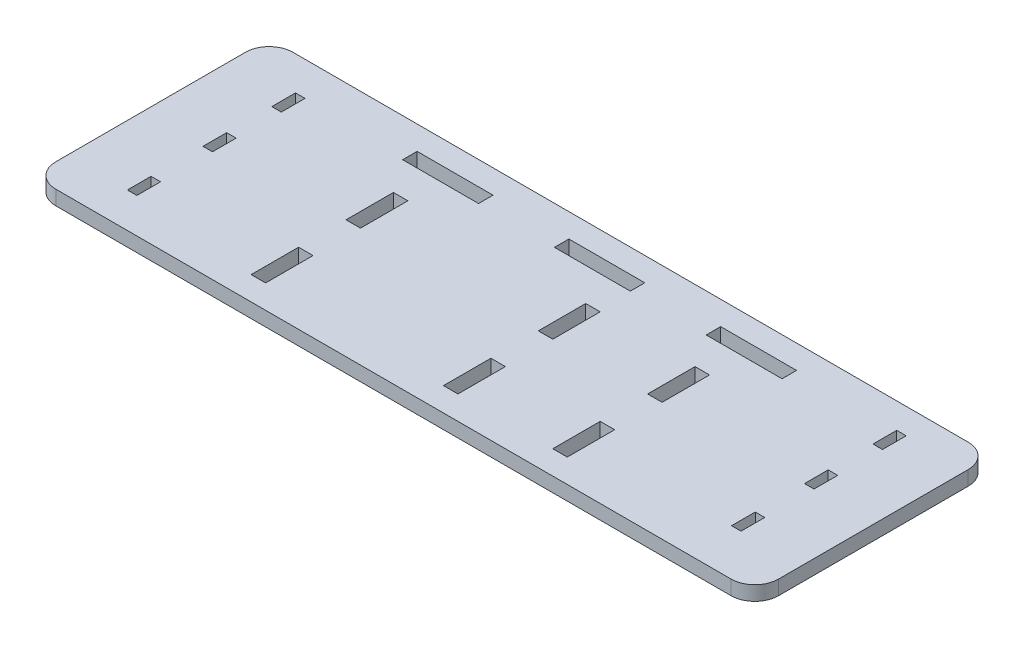
SolidWorks part; units mm, degrees
ref_plane "Front Plane" through (0, 0, 0) normal (0, 0, 1) x (1, 0, 0)
ref_plane "Top Plane" through (0, 0, 0) normal (0, 1, 0) x (1, 0, 0)
ref_plane "Right Plane" through (0, 0, 0) normal (1, 0, 0) x (0, 0, -1)
sketch "Sketch1" plane through (0, 0, 0) normal (0, 1, 0) x (1, 0, 0)
  line L0 (-232.4, 90) -> (-232.4, 83.9)
  line L1 (-294.8, 100) -> (-10, 100)
  line L2 (-304.8, 90) -> (-304.8, 10)
  line L3 (-294.8, 0) -> (-10, 0)
  line L4 (0, 90) -> (0, 10)
  line L5 (-232.4, 83.9) -> (-200.4, 83.9)
  line L6 (-200.4, 83.9) -> (-200.4, 90)
  line L7 (-200.4, 90) -> (-232.4, 90)
  line L8 (-168.4, 90) -> (-168.4, 83.9)
  line L9 (-168.4, 83.9) -> (-136.4, 83.9)
  line L10 (-136.4, 83.9) -> (-136.4, 90)
  line L11 (-136.4, 90) -> (-168.4, 90)
  line L12 (-104.4, 90) -> (-104.4, 83.9)
  line L13 (-104.4, 83.9) -> (-72.4, 83.9)
  line L14 (-72.4, 83.9) -> (-72.4, 90)
  line L15 (-72.4, 90) -> (-104.4, 90)
  line L16 (-200.4, 90) -> (-168.4, 90) construction
  line L17 (-168.4, 83.9) -> (-200.4, 83.9) construction
  line L18 (-136.4, 83.9) -> (-104.4, 83.9) construction
  line L19 (-104.4, 90) -> (-136.4, 90) construction
  line L20 (-152.4, 100) -> (-152.4, 90) construction
  line L21 (-168.4, 86.95) -> (-136.4, 86.95) construction
  line L22 (-152.4, 90) -> (-152.4, 86.95) construction
  line L23 (-152.4, 86.95) -> (-152.4, 83.9) construction
  line L24 (-152.4, 83.9) -> (-152.4, 0) construction
  line L25 (-216.3, 70) -> (-216.3, 90) construction
  line L26 (-222.4, 70) -> (-216.3, 70)
  line L27 (-222.4, 70) -> (-222.4, 50)
  line L28 (-222.4, 50) -> (-216.3, 50)
  line L29 (-216.3, 70) -> (-216.3, 50)
  line L30 (-222.4, 30) -> (-216.3, 30)
  line L31 (-222.4, 30) -> (-222.4, 10)
  line L32 (-222.4, 10) -> (-216.3, 10)
  line L33 (-216.3, 30) -> (-216.3, 10)
  line L34 (-216.3, 50) -> (-216.3, 30) construction
  line L35 (-29.4, 89.2391) -> (-25.4, 89.2391)
  line L36 (-135.2, 70) -> (-135.2, 90) construction
  line L37 (-141.3, 70) -> (-135.2, 70)
  line L38 (-141.3, 70) -> (-141.3, 50)
  line L39 (-141.3, 50) -> (-135.2, 50)
  line L40 (-135.2, 70) -> (-135.2, 50)
  line L41 (-141.3, 30) -> (-135.2, 30)
  line L42 (-141.3, 30) -> (-141.3, 10)
  line L43 (-141.3, 10) -> (-135.2, 10)
  line L44 (-135.2, 30) -> (-135.2, 10)
  line L45 (-135.2, 50) -> (-135.2, 30) construction
  line L46 (-279.4, 85.7039) -> (-275.4, 85.7039)
  line L47 (-89.1, 70) -> (-89.1, 90) construction
  line L48 (-95.2, 70) -> (-89.1, 70)
  line L49 (-95.2, 70) -> (-95.2, 50)
  line L50 (-95.2, 50) -> (-89.1, 50)
  line L51 (-89.1, 70) -> (-89.1, 50)
  line L52 (-95.2, 30) -> (-89.1, 30)
  line L53 (-95.2, 30) -> (-95.2, 10)
  line L54 (-95.2, 10) -> (-89.1, 10)
  line L55 (-89.1, 30) -> (-89.1, 10)
  line L56 (-89.1, 50) -> (-89.1, 30) construction
  line L57 (-279.4, 85.7039) -> (-279.4, 75.7039)
  line L58 (-279.4, 75.7039) -> (-275.4, 75.7039)
  line L59 (-275.4, 85.7039) -> (-275.4, 75.7039)
  line L60 (-279.4, 24.7964) -> (-275.4, 24.7964)
  line L61 (-279.4, 24.7964) -> (-279.4, 14.7964)
  line L62 (-279.4, 14.7964) -> (-275.4, 14.7964)
  line L63 (-275.4, 24.7964) -> (-275.4, 14.7964)
  line L64 (-279.4, 56.6779) -> (-275.4, 56.6779)
  line L65 (-279.4, 56.6779) -> (-279.4, 46.6779)
  line L66 (-279.4, 46.6779) -> (-275.4, 46.6779)
  line L67 (-275.4, 56.6779) -> (-275.4, 46.6779)
  line L68 (-29.4, 89.2391) -> (-29.4, 79.2391)
  line L69 (-29.4, 79.2391) -> (-25.4, 79.2391)
  line L70 (-25.4, 89.2391) -> (-25.4, 79.2391)
  line L71 (-29.4, 29.5818) -> (-25.4, 29.5818)
  line L72 (-29.4, 29.5818) -> (-29.4, 19.5818)
  line L73 (-29.4, 19.5818) -> (-25.4, 19.5818)
  line L74 (-25.4, 29.5818) -> (-25.4, 19.5818)
  line L75 (-29.4, 60.3583) -> (-25.4, 60.3583)
  line L76 (-29.4, 60.3583) -> (-29.4, 50.3583)
  line L77 (-29.4, 50.3583) -> (-25.4, 50.3583)
  line L78 (-25.4, 60.3583) -> (-25.4, 50.3583)
  arc A0 (-304.8, 90) -> (-294.8, 100) centre (-294.8, 90) cw
  arc A1 (-294.8, 0) -> (-304.8, 10) centre (-294.8, 10) cw
  arc A2 (0, 10) -> (-10, 0) centre (-10, 10) cw
  arc A3 (-10, 100) -> (0, 90) centre (-10, 90) cw
  point P7 (-304.8, 100)
  point P10 (-304.8, 0)
  point P13 (0, 0)
  dimension "D3" = 10
  dimension "D4" = 10
  dimension "D5" = 10
  dimension "D6" = 10
  dimension "D1" = 304.8
  dimension "D2" = 80
  dimension "D7" = 160
  dimension "D8" = 6.1
  dimension "D9" = 10
  dimension "D10" = 6.1
  dimension "D11" = 6.1
  dimension "D12" = 6.1
  dimension "D13" = 75
  dimension "D14" = 40
  dimension "D15" = 10
  dimension "D16" = 20
  dimension "D17" = 100
  dimension "D18" = 10
  dimension "D19" = 10
  dimension "D20" = 4
  dimension "D21" = 4
  dimension "D22" = 25.4
  dimension "D23" = 25.4
extrude "Boss-Extrude1" add sketch "Sketch1" along normal blind 6.096
equation "\"mat\"= 6.1"
